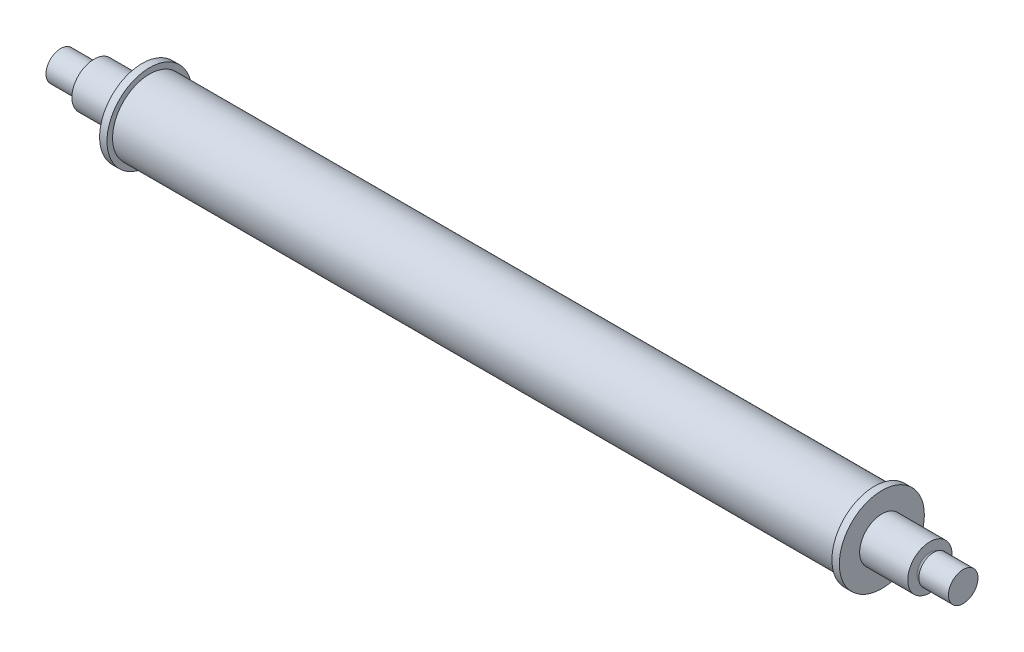
SolidWorks part; units mm, degrees
ref_plane "Front Plane" through (0, 0, 0) normal (0, 0, 1) x (1, 0, 0)
ref_plane "Top Plane" through (0, 0, 0) normal (0, 1, 0) x (1, 0, 0)
ref_plane "Right Plane" through (0, 0, 0) normal (1, 0, 0) x (0, 0, -1)
sketch "Sketch1" plane through (0, 0, 0) normal (0, 0, 1) x (1, 0, 0)
  line L0 (-122, 4) -> (-122, 0)
  line L1 (-122, 0) -> (122, 0)
  line L2 (122, 0) -> (122, 4)
  line L3 (122, 4) -> (114, 4)
  line L4 (114, 4) -> (114, 3.5)
  line L5 (113, 3.5) -> (113, 6)
  line L6 (113, 6) -> (100, 6)
  line L7 (100, 6) -> (100, 11.5)
  line L8 (100, 11.5) -> (98, 11.5)
  line L9 (98, 11.5) -> (98, 10)
  line L10 (98, 10) -> (-98, 10)
  line L11 (-98, 10) -> (-98, 11.5)
  line L12 (-98, 11.5) -> (-100, 11.5)
  line L13 (-100, 11.5) -> (-100, 6)
  line L14 (-100, 6) -> (-113, 6)
  line L15 (-113, 6) -> (-113, 3.5)
  line L16 (-114, 3.5) -> (-114, 4)
  line L17 (-114, 4) -> (-122, 4)
  line L18 (-122, 0) -> (122, 0) construction
  arc A0 (114, 3.5) -> (113, 3.5) centre (113.5, 3.5) cw
  arc A1 (-113, 3.5) -> (-114, 3.5) centre (-113.5, 3.5) cw
revolve "Revolve1" add sketch "Sketch1" angle 360 about L18
